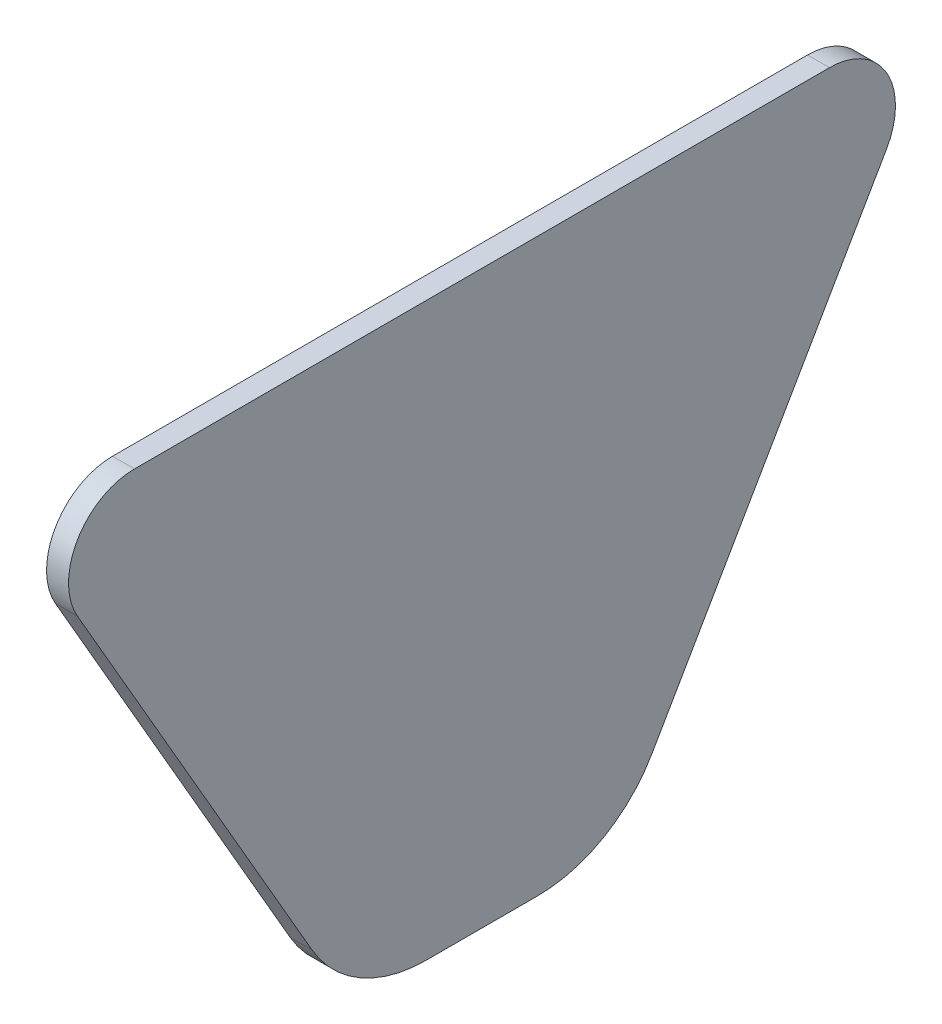
SolidWorks part; units mm, degrees
material "AISI 1020"
ref_plane "Спереди" through (0, 0, 0) normal (0, 0, 1) x (1, 0, 0)
ref_plane "Сверху" through (0, 0, 0) normal (0, 1, 0) x (1, 0, 0)
ref_plane "Справа" through (0, 0, 0) normal (1, 0, 0) x (0, 0, -1)
sketch "Эскиз1" plane through (0, 0, 0) normal (1, 0, 0) x (0, 0, -1)
  line L0 (-105.9379, 0) -> (112.882, 0) construction
  line L1 (0, 41.9876) -> (0, -88.0124) construction
  line L2 (2.5359, -52) -> (-2.5359, -52)
  line L3 (-7.7321, -49) -> (-18.413, -30.5)
  line L4 (-15.815, -26) -> (15.815, -26)
  line L5 (7.7321, -49) -> (18.413, -30.5)
  arc A0 (-15.815, -26) -> (-18.413, -30.5) centre (-15.815, -29) ccw
  arc A1 (-7.7321, -49) -> (-2.5359, -52) centre (-2.5359, -46) ccw
  arc A2 (7.7321, -49) -> (2.5359, -52) centre (2.5359, -46) cw
  arc A3 (15.815, -26) -> (18.413, -30.5) centre (15.815, -29) cw
  point P13 (-6, -52)
  point P15 (0, -52)
  point P20 (0, -26)
  dimension "D5" = 3
  dimension "D6" = 6
  dimension "D1" = 26
  dimension "D2" = 26
  dimension "D3" = 30
  dimension "D4" = 6
extrude "Бобышка-Вытянуть1" add sketch "Эскиз1" along normal mid plane 1
sketch "Эскиз2" plane through (-0.5, 0, 0) normal (-1, 0, 0) x (0, 0, 1)
  line L0 (-30.2907, 0) -> (28.9342, 0) construction
  line L1 (0, 19.4105) -> (0, -54.8494) construction
  line L2 (1.7287, -43) -> (-1.7287, -43)
  arc A0 (-2.2615, -43.1538) -> (-4.5486, -46.6876) centre (0.4026, -47.3849) ccw
  arc A1 (2.2615, -43.1538) -> (4.5486, -46.6876) centre (-0.4026, -47.3849) cw
  arc A2 (4.4479, -47.2839) -> (-4.4479, -47.2839) centre (0, -45) cw
  arc A3 (-4.4479, -47.2839) -> (-4.5486, -46.6876) centre (-3.5583, -46.8271) cw
  arc A4 (4.4479, -47.2839) -> (4.5486, -46.6876) centre (3.5583, -46.8271) ccw
  arc A5 (-2.2615, -43.1538) -> (-1.7287, -43) centre (-1.7287, -44) cw
  arc A6 (2.2615, -43.1538) -> (1.7287, -43) centre (1.7287, -44) ccw
  arc A7 (6.85, -30.4376) -> (12.7338, -29.0231) centre (0, 11) ccw
  arc A8 (7.2955, -41.6381) -> (3.9192, -38.1143) centre (6, -39.5) cw
  arc A9 (3.9192, -38.1143) -> (6.0133, -31.4066) centre (-6.4848, -31.1856) ccw
  arc A10 (14.0367, -30) -> (7.2955, -41.6381) centre (0.0407, -29.6645) cw
  arc A11 (6.0133, -31.4066) -> (6.85, -30.4376) centre (7.0131, -31.4242) cw
  arc A12 (12.7338, -29.0231) -> (14.0367, -30) centre (13.037, -29.9761) cw
  arc A13 (-3.9192, -38.1143) -> (-6.0133, -31.4066) centre (6.4848, -31.1856) cw
  arc A14 (-7.2955, -41.6381) -> (-3.9192, -38.1143) centre (-6, -39.5) ccw
  arc A15 (-14.0367, -30) -> (-7.2955, -41.6381) centre (-0.0407, -29.6645) ccw
  arc A16 (-12.7338, -29.0231) -> (-14.0367, -30) centre (-13.037, -29.9761) ccw
  arc A17 (-6.85, -30.4376) -> (-12.7338, -29.0231) centre (0, 11) cw
  arc A18 (-6.0133, -31.4066) -> (-6.85, -30.4376) centre (-7.0131, -31.4242) ccw
  point P12 (0, -43)
  point P16 (-4.5826, -47)
  point P19 (4.5826, -47)
  point P22 (-2, -43)
  point P25 (2, -43)
  point P35 (6, -30.5692)
  point P38 (14, -28.598)
  dimension "D4" = 5
  dimension "D5" = 5
  dimension "D7" = 1
  dimension "D9" = 42
  dimension "D14" = 2.5
  dimension "D15" = 12.5
  dimension "D16" = 14
  dimension "D17" = 1
  dimension "D1" = 43
  dimension "D2" = 2
  dimension "D3" = 4
  dimension "D6" = 2
  dimension "D8" = 11
  dimension "D10" = 6
  dimension "D11" = 14
  dimension "D12" = 3.5
  dimension "D13" = 6
extrude "Бобышка-Вытянуть2" add sketch "Эскиз2" along normal blind 2
fillet "Скругление1" radius 0.3 20 edges at (-2.5, -46.9936, -4.5444) (-2.5, -44.6683, -3.795) (-2.5, -43.0392, -2.006) (-2.5, -43, 0) (-2.5, -43.0392, 2.006) (-2.5, -44.6683, 3.795) (-2.5, -46.9936, 4.5444) (-2.5, -34.9106, 5.4473) (-2.5, -30.7706, 6.2563) (-2.5, -29.8365, 9.8174) (-2.5, -29.176, 13.6368) (-2.5, -36.6816, 12.1552) (-2.5, -29.176, -13.6368) (-2.5, -29.8365, -9.8174) (-2.5, -30.7706, -6.2563) (-2.5, -34.9106, -5.4473) (-2.5, -41.2296, -4.1948) (-2.5, -50, 0) (-2.5, -41.2296, 4.1948) (-2.5, -36.6816, -12.1552)
sketch "Эскиз3" plane through (-2.5, 0, 0) normal (-1, 0, 0) x (0, 0, 1)
  line L0 (0, 4.6019) -> (0, -59.7505) construction
  line L1 (1.7287, -43) -> (-1.7287, -43) construction
  line L2 (0, -44) -> (-2.4249, -48.2)
  line L3 (-2.4249, -48.2) -> (2.4249, -48.2)
  line L4 (2.4249, -48.2) -> (0, -44)
  line L5 (0, -46.8) -> (0.2288, -44.1843) construction
  line L6 (0, -44.4) -> (-2.0785, -48)
  line L7 (-2.0785, -48) -> (2.0785, -48)
  line L8 (2.0785, -48) -> (0, -44.4)
  line L9 (0, -46) -> (0.0523, -46.2023)
  line L10 (0, -46) -> (-0.0523, -46.2023)
  line L11 (0.1389, -46.0122) -> (0.0523, -46.2023)
  line L12 (0.1389, -46.0122) -> (0.1553, -46.2204)
  line L13 (8.9258, 3.821) -> (-2.2488, -59.5538) construction
  line L14 (0.2736, -46.0482) -> (0.1553, -46.2204)
  line L15 (0.2736, -46.0482) -> (0.2536, -46.2562)
  line L16 (17.5805, 1.502) -> (-4.4293, -58.9695) construction
  line L17 (0.4, -46.1072) -> (0.2536, -46.2562)
  line L18 (0.4, -46.1072) -> (0.3441, -46.3085)
  line L19 (25.701, -2.2846) -> (-6.4753, -58.0155) construction
  line L20 (0.5142, -46.1872) -> (0.3441, -46.3085)
  line L21 (0.5142, -46.1872) -> (0.4243, -46.3757)
  line L22 (33.0405, -7.4238) -> (-8.3244, -56.7207) construction
  line L23 (0.6128, -46.2858) -> (0.4243, -46.3757)
  line L24 (0.6128, -46.2858) -> (0.4915, -46.4559)
  line L25 (39.3762, -13.7595) -> (-9.9207, -55.1244) construction
  line L26 (0.6928, -46.4) -> (0.4915, -46.4559)
  line L27 (0.6928, -46.4) -> (0.5438, -46.5464)
  line L28 (44.5154, -21.099) -> (-11.2155, -53.2753) construction
  line L29 (0.7518, -46.5264) -> (0.5438, -46.5464)
  line L30 (0.7518, -46.5264) -> (0.5796, -46.6447)
  line L31 (48.302, -29.2195) -> (-12.1695, -51.2293) construction
  line L32 (0.7878, -46.6611) -> (0.5796, -46.6447)
  line L33 (0.7878, -46.6611) -> (0.5977, -46.7477)
  line L34 (50.621, -37.8742) -> (-12.7538, -49.0488) construction
  line L35 (0.8, -46.8) -> (0.5977, -46.7477)
  line L36 (0.8, -46.8) -> (0.5977, -46.8523)
  line L37 (51.4019, -46.8) -> (-12.9505, -46.8) construction
  line L38 (0.7878, -46.9389) -> (0.5977, -46.8523)
  line L39 (0.7878, -46.9389) -> (0.5796, -46.9553)
  line L40 (50.621, -55.7258) -> (-12.7538, -44.5512) construction
  line L41 (0.7518, -47.0736) -> (0.5796, -46.9553)
  line L42 (0.7518, -47.0736) -> (0.5438, -47.0536)
  line L43 (48.302, -64.3805) -> (-12.1695, -42.3707) construction
  line L44 (0.6928, -47.2) -> (0.5438, -47.0536)
  line L45 (0.6928, -47.2) -> (0.4915, -47.1441)
  line L46 (44.5154, -72.501) -> (-11.2155, -40.3247) construction
  line L47 (0.6128, -47.3142) -> (0.4915, -47.1441)
  line L48 (0.6128, -47.3142) -> (0.4243, -47.2243)
  line L49 (39.3762, -79.8405) -> (-9.9207, -38.4756) construction
  line L50 (0.5142, -47.4128) -> (0.4243, -47.2243)
  line L51 (0.5142, -47.4128) -> (0.3441, -47.2915)
  line L52 (33.0405, -86.1762) -> (-8.3244, -36.8793) construction
  line L53 (0.4, -47.4928) -> (0.3441, -47.2915)
  line L54 (0.4, -47.4928) -> (0.2536, -47.3438)
  line L55 (25.701, -91.3154) -> (-6.4753, -35.5845) construction
  line L56 (0.2736, -47.5518) -> (0.2536, -47.3438)
  line L57 (0.2736, -47.5518) -> (0.1553, -47.3796)
  line L58 (17.5805, -95.102) -> (-4.4293, -34.6305) construction
  line L59 (0.1389, -47.5878) -> (0.1553, -47.3796)
  line L60 (0.1389, -47.5878) -> (0.0523, -47.3977)
  line L61 (8.9258, -97.421) -> (-2.2488, -34.0462) construction
  line L62 (0, -47.6) -> (0.0523, -47.3977)
  line L63 (0, -47.6) -> (-0.0523, -47.3977)
  line L64 (0, -98.2019) -> (0, -33.8495) construction
  line L65 (-0.1389, -47.5878) -> (-0.0523, -47.3977)
  line L66 (-0.1389, -47.5878) -> (-0.1553, -47.3796)
  line L67 (-8.9258, -97.421) -> (2.2488, -34.0462) construction
  line L68 (-0.2736, -47.5518) -> (-0.1553, -47.3796)
  line L69 (-0.2736, -47.5518) -> (-0.2536, -47.3438)
  line L70 (-17.5805, -95.102) -> (4.4293, -34.6305) construction
  line L71 (-0.4, -47.4928) -> (-0.2536, -47.3438)
  line L72 (-0.4, -47.4928) -> (-0.3441, -47.2915)
  line L73 (-25.701, -91.3154) -> (6.4753, -35.5845) construction
  line L74 (-0.5142, -47.4128) -> (-0.3441, -47.2915)
  line L75 (-0.5142, -47.4128) -> (-0.4243, -47.2243)
  line L76 (-33.0405, -86.1762) -> (8.3244, -36.8793) construction
  line L77 (-0.6128, -47.3142) -> (-0.4243, -47.2243)
  line L78 (-0.6128, -47.3142) -> (-0.4915, -47.1441)
  line L79 (-39.3762, -79.8405) -> (9.9207, -38.4756) construction
  line L80 (-0.6928, -47.2) -> (-0.4915, -47.1441)
  line L81 (-0.6928, -47.2) -> (-0.5438, -47.0536)
  line L82 (-44.5154, -72.501) -> (11.2155, -40.3247) construction
  line L83 (-0.7518, -47.0736) -> (-0.5438, -47.0536)
  line L84 (-0.7518, -47.0736) -> (-0.5796, -46.9553)
  line L85 (-48.302, -64.3805) -> (12.1695, -42.3707) construction
  line L86 (-0.7878, -46.9389) -> (-0.5796, -46.9553)
  line L87 (-0.7878, -46.9389) -> (-0.5977, -46.8523)
  line L88 (-50.621, -55.7258) -> (12.7538, -44.5512) construction
  line L89 (-0.8, -46.8) -> (-0.5977, -46.8523)
  line L90 (-0.8, -46.8) -> (-0.5977, -46.7477)
  line L91 (-51.4019, -46.8) -> (12.9505, -46.8) construction
  line L92 (-0.7878, -46.6611) -> (-0.5977, -46.7477)
  line L93 (-0.7878, -46.6611) -> (-0.5796, -46.6447)
  line L94 (-50.621, -37.8742) -> (12.7538, -49.0488) construction
  line L95 (-0.7518, -46.5264) -> (-0.5796, -46.6447)
  line L96 (-0.7518, -46.5264) -> (-0.5438, -46.5464)
  line L97 (-48.302, -29.2195) -> (12.1695, -51.2293) construction
  line L98 (-0.6928, -46.4) -> (-0.5438, -46.5464)
  line L99 (-0.6928, -46.4) -> (-0.4915, -46.4559)
  line L100 (-44.5154, -21.099) -> (11.2155, -53.2753) construction
  line L101 (-0.6128, -46.2858) -> (-0.4915, -46.4559)
  line L102 (-0.6128, -46.2858) -> (-0.4243, -46.3757)
  line L103 (-39.3762, -13.7595) -> (9.9207, -55.1244) construction
  line L104 (-0.5142, -46.1872) -> (-0.4243, -46.3757)
  line L105 (-0.5142, -46.1872) -> (-0.3441, -46.3085)
  line L106 (-33.0405, -7.4238) -> (8.3244, -56.7207) construction
  line L107 (-0.4, -46.1072) -> (-0.3441, -46.3085)
  line L108 (-0.4, -46.1072) -> (-0.2536, -46.2562)
  line L109 (-25.701, -2.2846) -> (6.4753, -58.0155) construction
  line L110 (-0.2736, -46.0482) -> (-0.2536, -46.2562)
  line L111 (-0.2736, -46.0482) -> (-0.1553, -46.2204)
  line L112 (-17.5805, 1.502) -> (4.4293, -58.9695) construction
  line L113 (-0.1389, -46.0122) -> (-0.1553, -46.2204)
  line L114 (-0.1389, -46.0122) -> (-0.0523, -46.2023)
  line L115 (-8.9258, 3.821) -> (2.2488, -59.5538) construction
  circle A0 centre (0, -46.8) radius 1.4 construction
  circle A1 centre (0, -46.8) radius 1.2 construction
  point P196 (0, -46.8)
  dimension "D2" = 2.8
  dimension "D3" = 0.2
  dimension "D1" = 1
  dimension "D4" = 5
  dimension "D5" = 0.8
  dimension "D6" = 0.6
  dimension "D7" = 36
extrude "Вырез-Вытянуть1" cut sketch "Эскиз3" against normal blind 0.05 contours L3 L4 L2 L8 L7 L6 | L114 L113 L111 L110 L108 L107 L105 L104 L102 L101 L99 L98 L96 L95 L93 L92 L90 L89 L87 L86 L84 L83 L81 L80 L78 L77 L75 L74 L72 L71 L69 L68 L66 L65 L63 L62 L60 L59 L57 L56 L54 L53 L51 L50 L48 L47 L45 L44 L42 L41 L39
sketch "Эскиз4" plane through (-2.5, 0, 0) normal (-1, 0, 0) x (0, 0, 1)
  line L0 (0, 6.1709) -> (0, -56.1325) construction
  line L1 (-18.7811, 0) -> (21.2745, 0) construction
  line L2 (9, -29.785) -> (9, -40.1315) construction
  line L3 (8.3, -36.3266) -> (8.3, -37.7)
  line L4 (8.3, -37.7) -> (9.7, -37.7)
  line L5 (9.7, -36.3266) -> (9.7, -37.7)
  line L6 (9, -35) -> (5.2286, -37.1774) construction
  line L7 (7.3546, -35.95) -> (6.8349, -36.25) construction
  line L8 (7.4296, -36.0799) -> (6.9099, -36.3799)
  line L9 (7.2796, -35.8201) -> (6.7599, -36.1201)
  line L10 (9, -35) -> (4.7936, -36.1271) construction
  line L11 (7.1647, -35.4918) -> (6.5852, -35.647) construction
  line L12 (7.2036, -35.6366) -> (6.624, -35.7919)
  line L13 (7.1259, -35.3469) -> (6.5464, -35.5022)
  line L14 (9, -35) -> (4.6452, -35) construction
  line L15 (7.1, -35) -> (6.5, -35) construction
  line L16 (7.1, -35.15) -> (6.5, -35.15)
  line L17 (7.1, -34.85) -> (6.5, -34.85)
  line L18 (9, -35) -> (4.7936, -33.8729) construction
  line L19 (7.1647, -34.5082) -> (6.5852, -34.353) construction
  line L20 (7.1259, -34.6531) -> (6.5464, -34.4978)
  line L21 (7.2036, -34.3634) -> (6.624, -34.2081)
  line L22 (9, -35) -> (5.2286, -32.8226) construction
  line L23 (7.3546, -34.05) -> (6.8349, -33.75) construction
  line L24 (7.2796, -34.1799) -> (6.7599, -33.8799)
  line L25 (7.4296, -33.9201) -> (6.9099, -33.6201)
  line L26 (9, -35) -> (5.9207, -31.9207) construction
  line L27 (7.6565, -33.6565) -> (7.2322, -33.2322) construction
  line L28 (7.5504, -33.7626) -> (7.1262, -33.3383)
  line L29 (7.7626, -33.5504) -> (7.3383, -33.1262)
  line L30 (9, -35) -> (6.8226, -31.2286) construction
  line L31 (8.05, -33.3546) -> (7.75, -32.8349) construction
  line L32 (7.9201, -33.4296) -> (7.6201, -32.9099)
  line L33 (8.1799, -33.2796) -> (7.8799, -32.7599)
  line L34 (9, -35) -> (7.8729, -30.7936) construction
  line L35 (8.5082, -33.1647) -> (8.353, -32.5852) construction
  line L36 (8.3634, -33.2036) -> (8.2081, -32.624)
  line L37 (8.6531, -33.1259) -> (8.4978, -32.5464)
  line L38 (9, -35) -> (9, -30.6452) construction
  line L39 (9, -33.1) -> (9, -32.5) construction
  line L40 (8.85, -33.1) -> (8.85, -32.5)
  line L41 (9.15, -33.1) -> (9.15, -32.5)
  line L42 (9, -35) -> (10.1271, -30.7936) construction
  line L43 (9.4918, -33.1647) -> (9.647, -32.5852) construction
  line L44 (9.3469, -33.1259) -> (9.5022, -32.5464)
  line L45 (9.6366, -33.2036) -> (9.7919, -32.624)
  line L46 (9, -35) -> (11.1774, -31.2286) construction
  line L47 (9.95, -33.3546) -> (10.25, -32.8349) construction
  line L48 (9.8201, -33.2796) -> (10.1201, -32.7599)
  line L49 (10.0799, -33.4296) -> (10.3799, -32.9099)
  line L50 (9, -35) -> (12.0793, -31.9207) construction
  line L51 (10.3435, -33.6565) -> (10.7678, -33.2322) construction
  line L52 (10.2374, -33.5504) -> (10.6617, -33.1262)
  line L53 (10.4496, -33.7626) -> (10.8738, -33.3383)
  line L54 (9, -35) -> (12.7714, -32.8226) construction
  line L55 (10.6454, -34.05) -> (11.1651, -33.75) construction
  line L56 (10.5704, -33.9201) -> (11.0901, -33.6201)
  line L57 (10.7204, -34.1799) -> (11.2401, -33.8799)
  line L58 (9, -35) -> (13.2064, -33.8729) construction
  line L59 (10.8353, -34.5082) -> (11.4148, -34.353) construction
  line L60 (10.7964, -34.3634) -> (11.376, -34.2081)
  line L61 (10.8741, -34.6531) -> (11.4536, -34.4978)
  line L62 (9, -35) -> (13.3548, -35) construction
  line L63 (10.9, -35) -> (11.5, -35) construction
  line L64 (10.9, -34.85) -> (11.5, -34.85)
  line L65 (10.9, -35.15) -> (11.5, -35.15)
  line L66 (9, -35) -> (13.2064, -36.1271) construction
  line L67 (10.8353, -35.4918) -> (11.4148, -35.647) construction
  line L68 (10.8741, -35.3469) -> (11.4536, -35.5022)
  line L69 (10.7964, -35.6366) -> (11.376, -35.7919)
  line L70 (9, -35) -> (12.7714, -37.1774) construction
  line L71 (10.6454, -35.95) -> (11.1651, -36.25) construction
  line L72 (10.7204, -35.8201) -> (11.2401, -36.1201)
  line L73 (10.5704, -36.0799) -> (11.0901, -36.3799)
  line L74 (9, -35) -> (7.3546, -35.95) construction
  line L75 (9, -35) -> (7.1647, -35.4918) construction
  arc A0 (8.3, -36.3266) -> (9.7, -36.3266) centre (9, -35) cw
  arc A1 (7.4296, -36.0799) -> (7.2796, -35.8201) centre (7.3546, -35.95) ccw
  arc A2 (6.7599, -36.1201) -> (6.9099, -36.3799) centre (6.8349, -36.25) ccw
  arc A3 (7.2036, -35.6366) -> (7.1259, -35.3469) centre (7.1647, -35.4918) ccw
  arc A4 (6.5464, -35.5022) -> (6.624, -35.7919) centre (6.5852, -35.647) ccw
  arc A5 (7.1, -35.15) -> (7.1, -34.85) centre (7.1, -35) ccw
  arc A6 (6.5, -34.85) -> (6.5, -35.15) centre (6.5, -35) ccw
  arc A7 (7.1259, -34.6531) -> (7.2036, -34.3634) centre (7.1647, -34.5082) ccw
  arc A8 (6.624, -34.2081) -> (6.5464, -34.4978) centre (6.5852, -34.353) ccw
  arc A9 (7.2796, -34.1799) -> (7.4296, -33.9201) centre (7.3546, -34.05) ccw
  arc A10 (6.9099, -33.6201) -> (6.7599, -33.8799) centre (6.8349, -33.75) ccw
  arc A11 (7.5504, -33.7626) -> (7.7626, -33.5504) centre (7.6565, -33.6565) ccw
  arc A12 (7.3383, -33.1262) -> (7.1262, -33.3383) centre (7.2322, -33.2322) ccw
  arc A13 (7.9201, -33.4296) -> (8.1799, -33.2796) centre (8.05, -33.3546) ccw
  arc A14 (7.8799, -32.7599) -> (7.6201, -32.9099) centre (7.75, -32.8349) ccw
  arc A15 (8.3634, -33.2036) -> (8.6531, -33.1259) centre (8.5082, -33.1647) ccw
  arc A16 (8.4978, -32.5464) -> (8.2081, -32.624) centre (8.353, -32.5852) ccw
  arc A17 (8.85, -33.1) -> (9.15, -33.1) centre (9, -33.1) ccw
  arc A18 (9.15, -32.5) -> (8.85, -32.5) centre (9, -32.5) ccw
  arc A19 (9.3469, -33.1259) -> (9.6366, -33.2036) centre (9.4918, -33.1647) ccw
  arc A20 (9.7919, -32.624) -> (9.5022, -32.5464) centre (9.647, -32.5852) ccw
  arc A21 (9.8201, -33.2796) -> (10.0799, -33.4296) centre (9.95, -33.3546) ccw
  arc A22 (10.3799, -32.9099) -> (10.1201, -32.7599) centre (10.25, -32.8349) ccw
  arc A23 (10.2374, -33.5504) -> (10.4496, -33.7626) centre (10.3435, -33.6565) ccw
  arc A24 (10.8738, -33.3383) -> (10.6617, -33.1262) centre (10.7678, -33.2322) ccw
  arc A25 (10.5704, -33.9201) -> (10.7204, -34.1799) centre (10.6454, -34.05) ccw
  arc A26 (11.2401, -33.8799) -> (11.0901, -33.6201) centre (11.1651, -33.75) ccw
  arc A27 (10.7964, -34.3634) -> (10.8741, -34.6531) centre (10.8353, -34.5082) ccw
  arc A28 (11.4536, -34.4978) -> (11.376, -34.2081) centre (11.4148, -34.353) ccw
  arc A29 (10.9, -34.85) -> (10.9, -35.15) centre (10.9, -35) ccw
  arc A30 (11.5, -35.15) -> (11.5, -34.85) centre (11.5, -35) ccw
  arc A31 (10.8741, -35.3469) -> (10.7964, -35.6366) centre (10.8353, -35.4918) ccw
  arc A32 (11.376, -35.7919) -> (11.4536, -35.5022) centre (11.4148, -35.647) ccw
  arc A33 (10.7204, -35.8201) -> (10.5704, -36.0799) centre (10.6454, -35.95) ccw
  arc A34 (11.0901, -36.3799) -> (11.2401, -36.1201) centre (11.1651, -36.25) ccw
  point P12 (9, -37.7)
  point P16 (7.0947, -36.1)
  point P27 (6.875, -35.5694)
  point P35 (6.8, -35)
  point P43 (6.875, -34.4306)
  point P51 (7.0947, -33.9)
  point P59 (7.4444, -33.4444)
  point P67 (7.9, -33.0947)
  point P75 (8.4306, -32.875)
  point P83 (9, -32.8)
  point P91 (9.5694, -32.875)
  point P99 (10.1, -33.0947)
  point P107 (10.5556, -33.4444)
  point P115 (10.9053, -33.9)
  point P123 (11.125, -34.4306)
  point P131 (11.2, -35)
  point P139 (11.125, -35.5694)
  point P147 (10.9053, -36.1)
  dimension "D3" = 1.5
  dimension "D8" = 0.15
  dimension "D1" = 9
  dimension "D2" = 35
  dimension "D4" = 0.7
  dimension "D5" = 2.7
  dimension "D6" = 60
  dimension "D7" = 2.2
  dimension "D9" = 0.6
  dimension "D11" = 15
  dimension "D10" = 17
extrude "Вырез-Вытянуть2" cut sketch "Эскиз4" against normal blind 0.05
sketch "Эскиз5" plane through (-2.5, 0, 0) normal (-1, 0, 0) x (0, 0, 1)
  line L0 (-15.5093, 0) -> (14.9401, 0) construction
  line L1 (-7.14, -41.3816) -> (-13.7368, -29.9928) construction
  line L2 (-13.7198, -30.4212) -> (-7.5031, -41.1537) construction
  arc A0 (-13.7368, -29.9928) -> (-7.14, -41.3816) centre (-0.0407, -29.6645) ccw construction
  text T0 "   C/ F" font "Arial" height 3
  point P12 (0, 0)
  point P13 (0, 0)
  dimension "D1" = 0.2
extrude "Вырез-Вытянуть3" cut sketch "Эскиз5" against normal blind 0.05
sketch "Эскиз6" plane through (-2.5, 0, 0) normal (-1, 0, 0) x (0, 0, 1)
  line L0 (-29.1933, 0) -> (36.0966, 0) construction
  line L1 (-7.14, -41.3816) -> (-13.7368, -29.9928) construction
  line L2 (-9.1544, -38.3026) -> (-6.5937, -36.8177) construction
  line L3 (-7.0218, -36.1989) -> (-9.5279, -31.8723) construction
  circle A0 centre (-7.0218, -36.1989) radius 0.4
  circle A1 centre (-7.0218, -36.1989) radius 0.3
  circle A2 centre (-9.5279, -31.8723) radius 0.4
  circle A3 centre (-9.5279, -31.8723) radius 0.3
  dimension "D3" = 0.8
  dimension "D4" = 0.1
  dimension "D6" = 0.8
  dimension "D7" = 0.1
  dimension "D1" = 2.7
  dimension "D2" = 0.75
  dimension "D5" = 5
extrude "Вырез-Вытянуть4" cut sketch "Эскиз6" against normal blind 0.05
